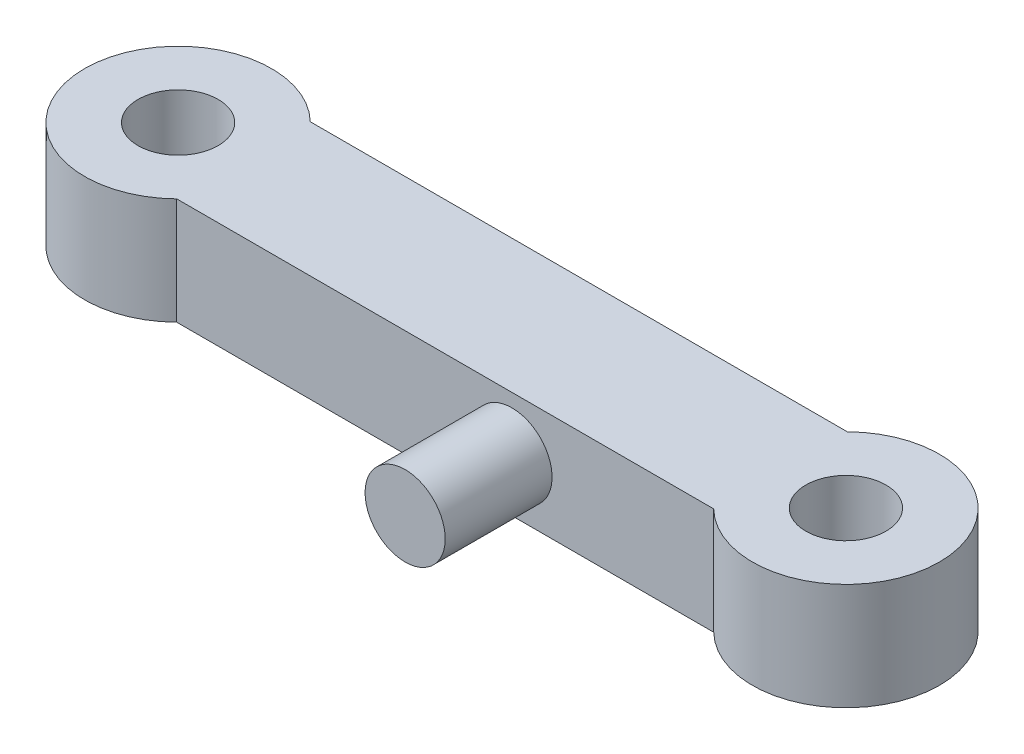
SolidWorks part; units mm, degrees
ref_plane "Спереди" through (0, 0, 0) normal (0, 0, 1) x (1, 0, 0)
ref_plane "Сверху" through (0, 0, 0) normal (0, 1, 0) x (1, 0, 0)
ref_plane "Справа" through (0, 0, 0) normal (1, 0, 0) x (0, 0, -1)
sketch "Эскиз1" plane through (0, 0, 0) normal (0, 1, 0) x (1, 0, 0)
  line L5 (-10.0505, -2.5) -> (10.0505, -2.5)
  line L7 (-10.0505, 2.5) -> (10.0505, 2.5)
  line L9 (-10.0505, -2.5) -> (10.0505, 2.5) construction
  line L10 (-10.0505, 2.5) -> (10.0505, -2.5) construction
  arc A0 (-10.0505, -2.5) -> (-10.0505, 2.5) centre (-12.5, 0) cw
  circle A1 centre (-12.5, 0) radius 1.5
  arc A2 (10.0505, 2.5) -> (10.0505, -2.5) centre (12.5, 0) cw
  circle A3 centre (12.5, 0) radius 1.5
  point P0 (0, 0)
  dimension "D1" = 3.5
  dimension "D3" = 3
  dimension "D4" = 25
  dimension "D2" = 5
extrude "Бобышка-Вытянуть1" add sketch "Эскиз1" along normal blind 4
sketch "Эскиз2" plane through (0, 0, 2.5) normal (0, 0, 1) x (1, 0, 0)
  line L1 (-989.9495, 2) -> (49010.0505, 2) construction
  line L2 (10.0505, 4) -> (10.0505, 0) construction
  circle A0 centre (2.5, 2) radius 1.5
  point P8 (10.0505, 2)
  dimension "D2" = 3
  dimension "D1" = 2.5
extrude "Бобышка-Вытянуть2" add sketch "Эскиз2" along normal blind 4
